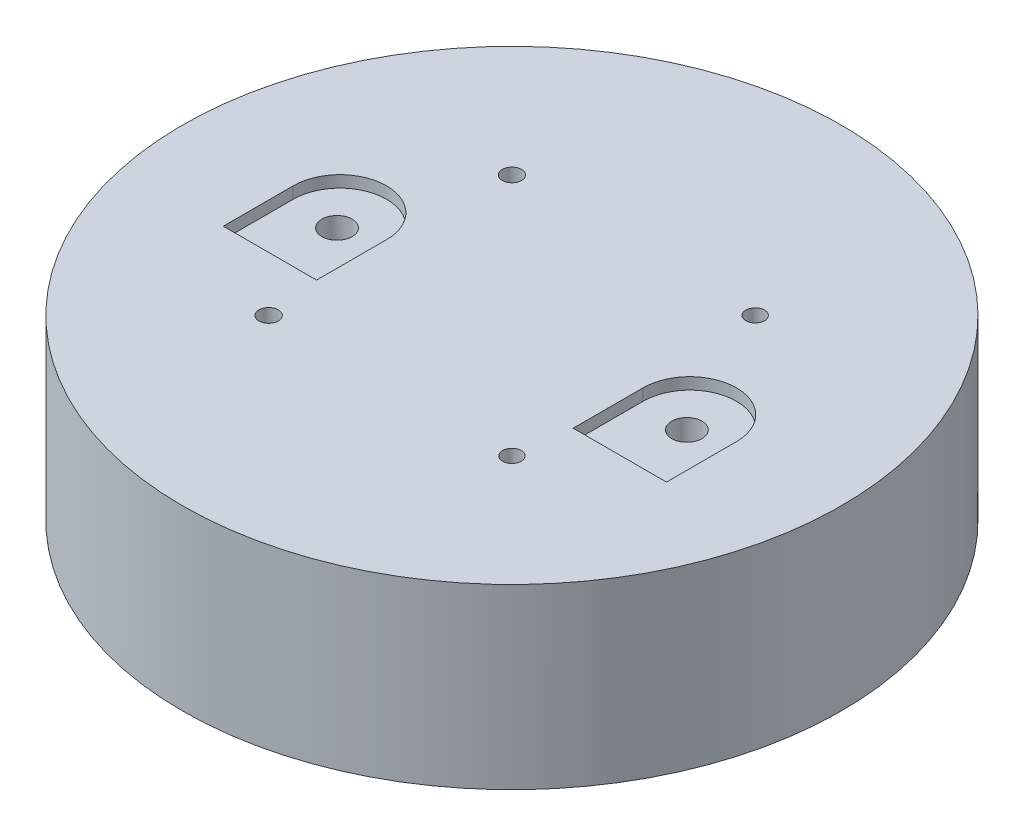
SolidWorks part; units mm, degrees
ref_plane "Front Plane" through (0, 0, 0) normal (0, 0, 1) x (1, 0, 0)
ref_plane "Top Plane" through (0, 0, 0) normal (0, 1, 0) x (1, 0, 0)
ref_plane "Right Plane" through (0, 0, 0) normal (1, 0, 0) x (0, 0, -1)
sketch "Sketch2" plane through (0, 0, 0) normal (0, 1, 0) x (1, 0, 0)
  line L0 (0, 0) -> (0, 56.515)
  circle A0 centre (0, 0) radius 51.435
  circle A1 centre (0, 0) radius 56.515
  circle A2 centre (0, 0) radius 47.2017
  circle A3 centre (0, 0) radius 42.1217
  dimension "D1" = 14.3933
  dimension "D2" = 5.08
  dimension "D3" = 4.2333
  dimension "D4" = 5.08
  dimension "D5" = 102.87
  dimension "D6" = 94.4033
extrude "Boss-Extrude1" add sketch "Sketch2" along normal blind 15.24 contours A1 A0 | A2 A3
sketch "Sketch3" plane through (0, 15.24, 0) normal (0, 1, 0) x (1, 0, 0)
  circle A0 centre (0, 0) radius 56.515
  dimension "D1" = 113.03
extrude "Boss-Extrude2" add sketch "Sketch3" along normal blind 15.24
sketch "Sketch4" plane through (0, 30.48, 0) normal (0, 1, 0) x (1, 0, 0)
  line L0 (0, 37.845) -> (0, -37.845) construction
  line L1 (37.845, 0) -> (-37.845, 0) construction
  line L2 (26.7605, 26.7605) -> (-26.7605, -26.7605) construction
  line L3 (-26.7605, 26.7605) -> (26.7605, -26.7605) construction
  circle A0 centre (0, 0) radius 37.845 construction
  circle A1 centre (0, 0) radius 29.5 construction
  circle A2 centre (20.8597, 20.8597) radius 1.6
  circle A3 centre (20.8597, -20.8597) radius 1.6
  circle A4 centre (-20.8597, -20.8597) radius 1.6588
  circle A5 centre (-20.8597, 20.8597) radius 1.651
  point P7 (0, 0)
  point P10 (0, 0)
  point P13 (0, 0)
  point P16 (0, 0)
  dimension "D1" = 75.69
  dimension "D2" = 59
  dimension "D3" = 45
  dimension "D4" = 45
  dimension "D5" = 3.2
  dimension "D6" = 3.2
  dimension "D7" = 3.3175
  dimension "D8" = 3.302
extrude "Cut-Extrude1" cut sketch "Sketch4" against normal through all both and the other way through all
sketch "Sketch5" plane through (0, 0, 0) normal (0, -1, 0) x (-1, 0, 0)
  line L0 (0, 0) -> (0, 29.5)
  line L1 (13.9476, 25) -> (-13.9476, 25)
  circle A1 centre (0, 0) radius 37.845
  circle A2 centre (0, 0) radius 29.5
  arc A3 (-13.9476, 54.7669) -> (13.9476, 54.7669) centre (0, 0) cw
  circle A4 centre (0, 0) radius 56.515 construction
  point P9 (0, 25)
  dimension "D1" = 75.69
  dimension "D2" = 59
  dimension "D3" = 25
  dimension "D4" = 31.515
ref_plane "Plane1" through (0, 0, -56.515) normal (0, 0, 1) x (1, 0, 0)
sketch "Sketch6" plane through (0, 30.48, 0) normal (0, 1, 0) x (1, 0, 0)
  line L0 (0, 0) -> (0, 56.515) construction
  line L1 (0, 0) -> (0, -56.515) construction
  line L2 (-56.515, 0) -> (56.515, 0) construction
  circle A0 centre (0, 0) radius 56.515 construction
  circle A1 centre (0, 30.48) radius 2.6
  circle A2 centre (0, -30.48) radius 2.6
  point P10 (0, 0)
  dimension "D2" = 5.2
  dimension "D3" = 5.2
  dimension "D1" = 113.03
  dimension "D4" = 30.48
  dimension "D5" = 30.48
ref_plane "Plane3" through (0, 0, -47.244) normal (0, 0, 1) x (1, 0, 0)
ref_plane "Plane4" through (17.78, 0, 0) normal (1, 0, 0) x (0, 0, -1)
sketch "Sketch13" plane through (0, 0, -56.515) normal (0, 0, 1) x (1, 0, 0)
  line L0 (0, 0) -> (0, 32.5704) construction
sketch "Sketch14" plane through (0, 0, -56.515) normal (0, 0, 1) x (1, 0, 0)
  line L0 (0, 0) -> (0, 30.48) construction
  line L1 (-56.515, 0) -> (56.515, 0) construction
  line L2 (56.515, 30.48) -> (-56.515, 30.48) construction
  line L3 (0, 15.24) -> (-5.7214, 15.24) construction
  circle A0 centre (0, 5.08) radius 10
  dimension "D3" = 20
  dimension "D1" = 15.24
  dimension "D2" = 10.16
extrude "Cut-Extrude7" cut sketch "Sketch14" along normal blind 19.558
sketch "Sketch16" plane through (0, 0, -56.515) normal (0, 0, 1) x (1, 0, 0)
  line L0 (0, 0) -> (0, 15.24) construction
  line L1 (0, 5.08) -> (0, 15.24) construction
  line L3 (0, 0) -> (0, 1.27)
  line L4 (9.2458, 1.27) -> (-9.2458, 1.27)
  arc A1 (9.2458, 1.27) -> (-9.2458, 1.27) centre (0, 5.08) ccw
  point P12 (0, 1.27)
  dimension "D1" = 10.16
  dimension "D2" = 1.27
  dimension "D3" = 15.24
extrude "Extrude-Thin1" add sketch "Sketch16" along normal blind 15.24 thin thin type one direction wall 1.27
sketch "Sketch20" plane through (0, 0, 0) normal (0, -1, 0) x (-1, 0, 0)
  circle A0 centre (0, 0) radius 56.515
extrude "Cut-Extrude-Thin3" cut sketch "Sketch20" against normal blind 15.748 thin
sketch "Sketch21" plane through (0, 0, -56.515) normal (0, 0, 1) x (1, 0, 0)
  line L0 (-9.3037, 0) -> (-9.2458, 1.27)
  line L1 (-56.515, 0) -> (56.515, 0) construction
  line L2 (-9.2458, 1.27) -> (9.2458, 1.27)
  line L3 (9.2458, 1.27) -> (-9.2458, 1.27) construction
  line L4 (9.2458, 1.27) -> (9.2458, 0)
  line L5 (9.2458, 0) -> (-9.3037, 0)
  arc A0 (8.6136, 0) -> (8.4029, 10.5013) centre (0, 5.08) ccw construction
extrude "Cut-Extrude12" cut sketch "Sketch21" along normal blind 15.748
sketch "Sketch32" plane through (0, 30.48, 0) normal (0, 1, 0) x (1, 0, 0)
  line L0 (0, 56.515) -> (0, -56.515) construction
  line L1 (-56.515, 0) -> (56.515, 0) construction
  line L2 (-30, 0.5) -> (-30, 0) construction
  line L3 (-22, 0.5) -> (-22, -11.5)
  line L4 (-38, 0.5) -> (-38, -11.5)
  line L5 (-38, -11.5) -> (-22, -11.5) construction
  line L6 (38, -11.5) -> (22, -11.5) construction
  line L7 (30, 0.5) -> (30, 0) construction
  line L8 (38, 0.5) -> (38, -11.5)
  line L9 (22, 0.5) -> (22, -11.5)
  line L10 (-38, -11.5) -> (-22, -11.5)
  line L11 (22, -11.5) -> (38, -11.5)
  circle A0 centre (0, 0) radius 56.515 construction
  arc A1 (-22, 0.5) -> (-38, 0.5) centre (-30, 0.5) ccw
  circle A4 centre (-30, 0) radius 2.6
  circle A5 centre (30, 0) radius 2.6
  arc A6 (22, 0.5) -> (38, 0.5) centre (30, 0.5) cw
  point P9 (-28.7356, -11.5)
  point P23 (28.7356, -11.5)
  dimension "D3" = 5.2
  dimension "D1" = 30
  dimension "D2" = 16
extrude "Cut-Extrude18" cut sketch "Sketch32" against normal blind 2
sketch "Sketch33" plane through (0, 30.48, 0) normal (0, 1, 0) x (1, 0, 0)
  circle A0 centre (-30, 0) radius 2.6
  circle A1 centre (30, 0) radius 2.6
extrude "Cut-Extrude19" cut sketch "Sketch33" against normal through all both and the other way through all
sketch "Sketch34" plane through (0, 15.24, 0) normal (0, -1, 0) x (-1, 0, 0)
  circle A0 centre (30, 0) radius 6
  circle A1 centre (-30, 0) radius 6
  dimension "D1" = 12
  dimension "D2" = 12
extrude "Cut-Extrude20" cut sketch "Sketch34" against normal blind 5
sketch "Sketch35" plane through (0, 20.24, 0) normal (0, -1, 0) x (-1, 0, 0)
  circle A0 centre (30, 0) radius 4.5219
